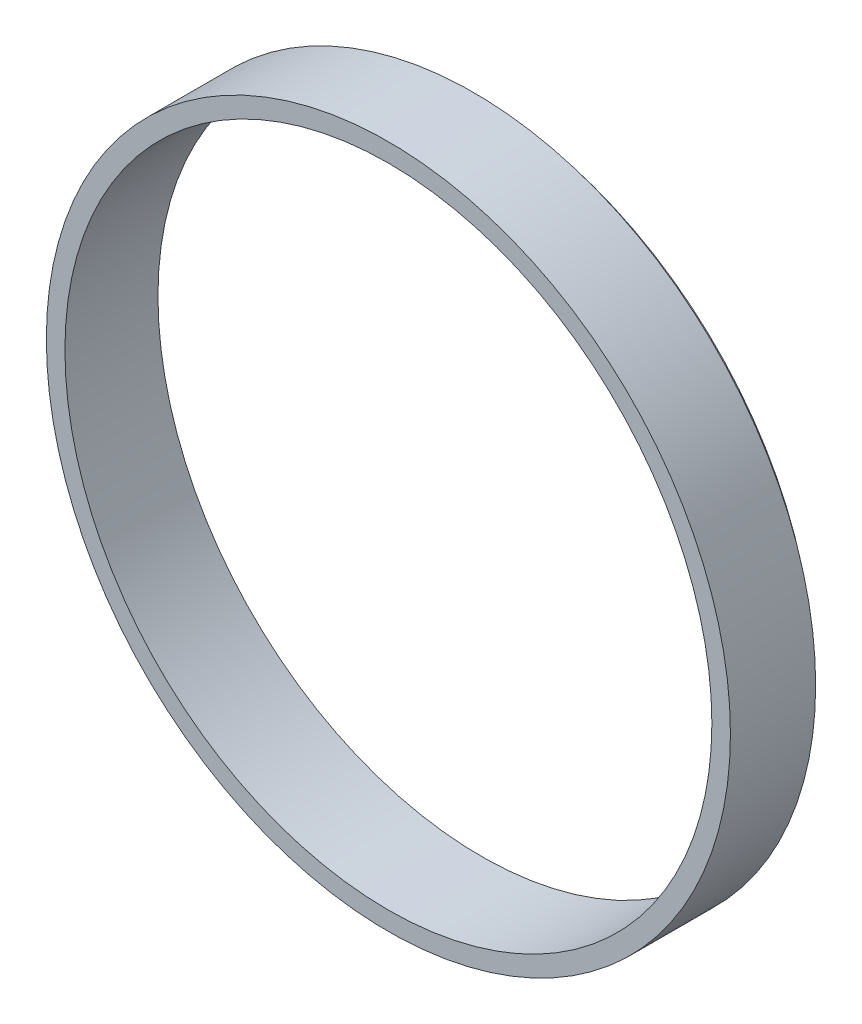
SolidWorks part; units mm, degrees
ref_plane "Front Plane" through (0, 0, 0) normal (0, 0, 1) x (1, 0, 0)
ref_plane "Top Plane" through (0, 0, 0) normal (0, 1, 0) x (1, 0, 0)
ref_plane "Right Plane" through (0, 0, 0) normal (1, 0, 0) x (0, 0, -1)
sketch "Sketch1" plane through (0, 0, 0) normal (0, 0, 1) x (1, 0, 0)
  circle A0 centre (0, 0) radius 87.5
  circle A1 centre (0, 0) radius 83.75
  dimension "D1" = 175
  dimension "D2" = 167.5
extrude "Boss-Extrude1" add sketch "Sketch1" along normal up to surface (21.8 mm away)
sketch "Sketch2" plane through (0, 0, 0) normal (0, 0, -1) x (-1, 0, 0)
  circle A0 centre (0, 0) radius 85
  circle A2 centre (0, 0) radius 82.75
  dimension "D1" = 170
  dimension "D2" = 165.5
extrude "Boss-Extrude2" add sketch "Sketch2" along normal blind 2 and the other way up to surface other way up to face at (83.75, 0, 21.8)
